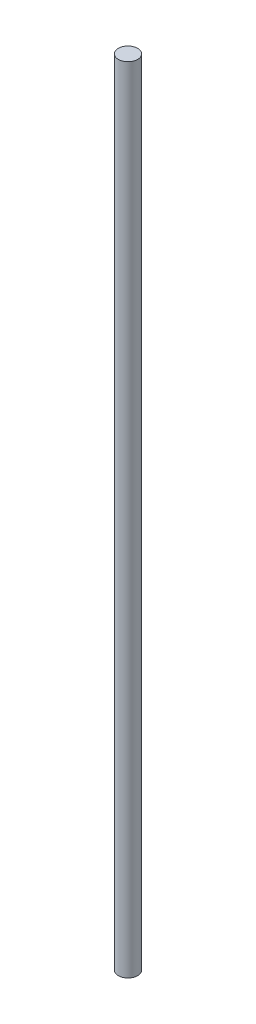
SolidWorks part; units mm, degrees
ref_plane "Front Plane" through (0, 0, 0) normal (0, 0, 1) x (1, 0, 0)
ref_plane "Top Plane" through (0, 0, 0) normal (0, 1, 0) x (1, 0, 0)
ref_plane "Right Plane" through (0, 0, 0) normal (1, 0, 0) x (0, 0, -1)
sketch "Sketch2" plane through (0, 0, 0) normal (0, 1, 0) x (1, 0, 0)
  circle A0 centre (0, 0) radius 1.0795
  dimension "D1" = 2.159
extrude "Boss-Extrude1" add sketch "Sketch2" along normal blind 88.9
equation "\"rodThick\"= 0.085in"
equation "\"thick\"= 0.122in"
equation "\"clear\"= 0.003in"
equation "\"D1@Sketch2\"=\"rodThick\""
